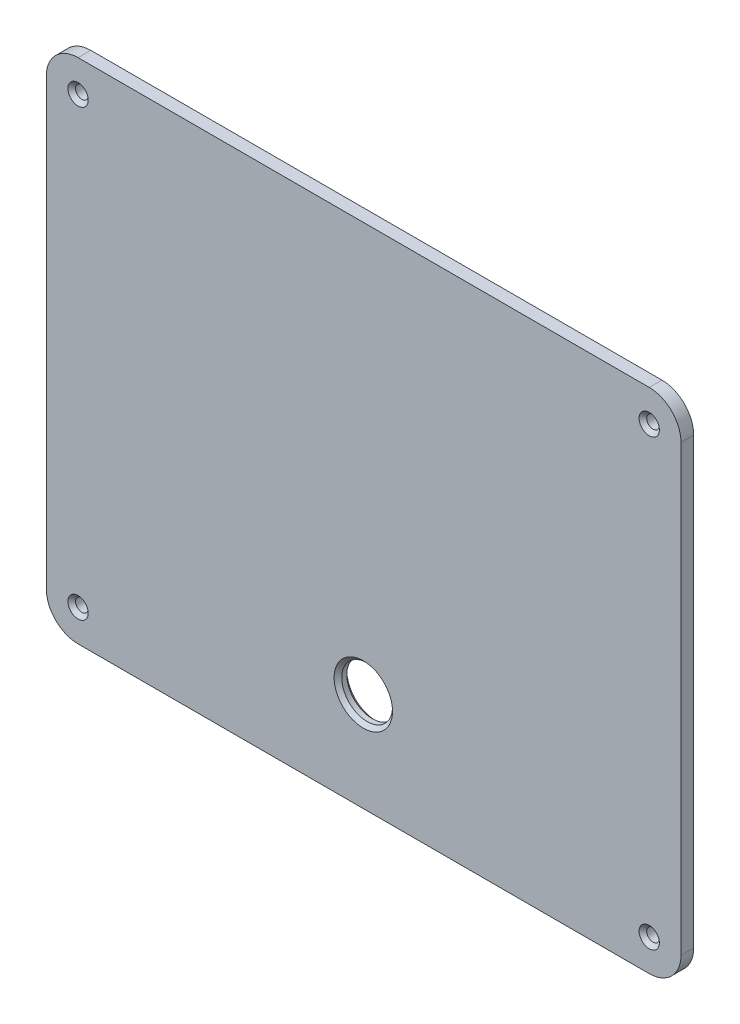
SolidWorks part; units mm, degrees
ref_plane "Plan de face" through (0, 0, 0) normal (0, 0, 1) x (1, 0, 0)
ref_plane "Plan de dessus" through (0, 0, 0) normal (0, 1, 0) x (1, 0, 0)
ref_plane "Plan de droite" through (0, 0, 0) normal (1, 0, 0) x (0, 0, -1)
sketch "Esquisse1" plane through (0, 0, 0) normal (0, 0, 1) x (1, 0, 0)
  line L0 (-224.723, -199.0305) -> (225.277, -199.0305)
  line L1 (250.277, -174.0305) -> (250.277, 175.9695)
  line L2 (225.277, 200.9695) -> (-224.723, 200.9695)
  line L3 (-249.723, 175.9695) -> (-249.723, -174.0305)
  arc A0 (225.277, -199.0305) -> (250.277, -174.0305) centre (225.277, -174.0305) ccw
  arc A1 (250.277, 175.9695) -> (225.277, 200.9695) centre (225.277, 175.9695) ccw
  arc A2 (-224.723, 200.9695) -> (-249.723, 175.9695) centre (-224.723, 175.9695) ccw
  arc A3 (-249.723, -174.0305) -> (-224.723, -199.0305) centre (-224.723, -174.0305) ccw
extrude "Boss.-Extru.1" add sketch "Esquisse1" along normal blind 10
sketch "Esquisse3" plane through (0, 0, 10) normal (0, 0, 1) x (1, 0, 0)
  line L4 (-224.723, -199.0305) -> (225.277, -199.0305)
  line L5 (250.277, -174.0305) -> (250.277, 175.9695)
  line L6 (225.277, 200.9695) -> (-224.723, 200.9695)
  line L7 (-249.723, 175.9695) -> (-249.723, -174.0305)
  circle A0 centre (-224.723, 175.9695) radius 5
  circle A1 centre (225.277, 175.9695) radius 5
  circle A2 centre (225.277, -174.0305) radius 5
  circle A3 centre (-224.723, -174.0305) radius 5
  arc A4 (-249.723, -174.0305) -> (-224.723, -199.0305) centre (-224.723, -174.0305) ccw
  arc A5 (225.277, -199.0305) -> (250.277, -174.0305) centre (225.277, -174.0305) ccw
  arc A6 (250.277, 175.9695) -> (225.277, 200.9695) centre (225.277, 175.9695) ccw
  arc A7 (-224.723, 200.9695) -> (-249.723, 175.9695) centre (-224.723, 175.9695) ccw
  arc A8 (-249.723, -174.0305) -> (-224.723, -199.0305) centre (-224.723, -174.0305) ccw
  arc A9 (225.277, -199.0305) -> (250.277, -174.0305) centre (225.277, -174.0305) ccw
  arc A10 (250.277, 175.9695) -> (225.277, 200.9695) centre (225.277, 175.9695) ccw
  arc A11 (-224.723, 200.9695) -> (-249.723, 175.9695) centre (-224.723, 175.9695) ccw
  dimension "D2" = 10
  dimension "D1" = 0
extrude "Enlèv. mat.-Extru.1" cut sketch "Esquisse3" against normal blind 10 contours A3 | A2 | A1 | A0
chamfer "Chanfrein1" distance 3 angle 45 4 edges at (230.277, 175.9695, 10) (230.277, -174.0305, 10) (-219.723, -174.0305, 10) (-219.723, 175.9695, 10)
sketch "Esquisse4" plane through (0, 0, 10) normal (0, 0, 1) x (1, 0, 0)
  line L1 (-224.723, -199.0305) -> (225.277, -199.0305) construction
  circle A0 centre (0, -121.1605) radius 20
  point P4 (0, 0)
  dimension "D2" = 40
  dimension "D1" = 77.87
extrude "Enlèv. mat.-Extru.2" cut sketch "Esquisse4" against normal blind 10
chamfer "Chanfrein2" distance 3 angle 45 2 edges at (20, -121.1605, 10) (20, -121.1605, 0)
